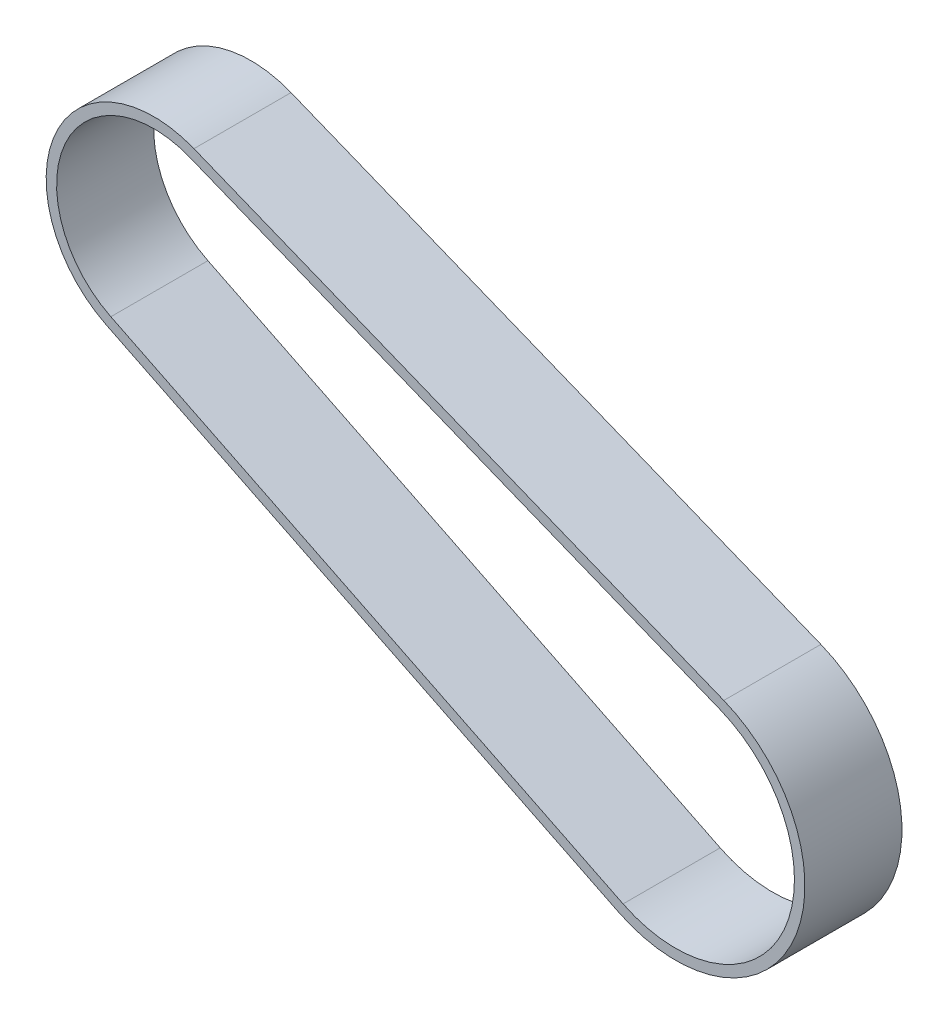
SolidWorks part; units mm, degrees
ref_plane "Front" through (0, 0, 0) normal (0, 0, 1) x (1, 0, 0)
ref_plane "Top" through (0, 0, 0) normal (0, 1, 0) x (1, 0, 0)
ref_plane "Right" through (0, 0, 0) normal (1, 0, 0) x (0, 0, -1)
sketch "Sketch1" plane through (0, 0, 0) normal (0, 0, 1) x (1, 0, 0)
  line L0 (193.3627, -139.9189) -> (-17.7025, -35.9308)
  line L1 (14.9344, 37.1667) -> (233.2595, -50.5612)
  line L2 (-19.6029, -39.7881) -> (191.4623, -143.7761)
  line L3 (234.8627, -46.5712) -> (16.5377, 41.1567)
  line L4 (0, 0) -> (66.7324, 0) construction
  line L5 (0, 0) -> (215.003, -95.9954) construction
  arc A0 (-17.7025, -35.9308) -> (14.9344, 37.1667) centre (0, 0) cw
  arc A1 (233.2595, -50.5612) -> (193.3627, -139.9189) centre (215.003, -95.9954) cw
  arc A2 (191.4623, -143.7761) -> (234.8627, -46.5712) centre (215.003, -95.9954) ccw
  arc A3 (16.5377, 41.1567) -> (-19.6029, -39.7881) centre (0, 0) ccw
  dimension "D2" = 40.055
  dimension "D3" = 44.355
  dimension "D4" = 48.965
  dimension "D5" = 53.265
  dimension "D1" = 24.06
  dimension "D6" = 235.46
extrude "Boss-Extrude1" add sketch "Sketch1" along normal blind 40
